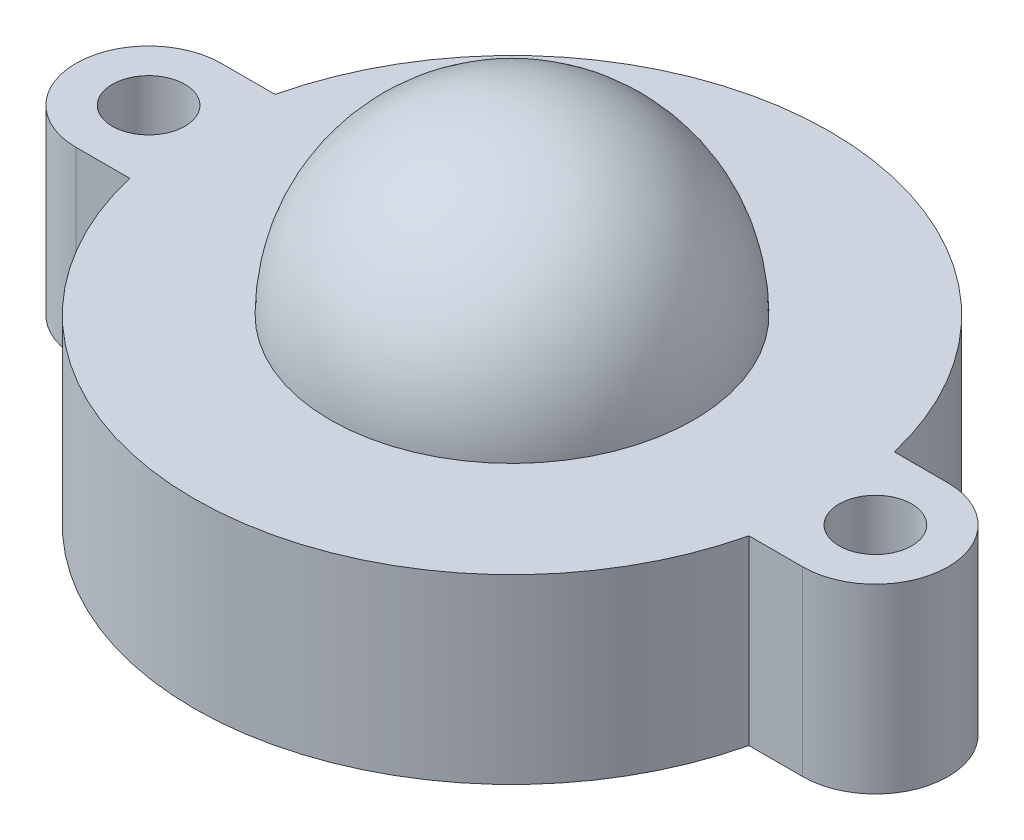
SolidWorks part; units mm, degrees
material "Chrome Stainless Steel"
ref_plane "Front Plane" through (0, 0, 0) normal (0, 0, 1) x (1, 0, 0)
ref_plane "Top Plane" through (0, 0, 0) normal (0, 1, 0) x (1, 0, 0)
ref_plane "Right Plane" through (0, 0, 0) normal (1, 0, 0) x (0, 0, -1)
sketch "Sketch1" plane through (0, 0, 0) normal (0, 1, 0) x (1, 0, 0)
  line L1 (-20, -4) -> (20, -4)
  line L2 (-20, -4) -> (-20, 4)
  line L3 (-20, 4) -> (20, 4)
  line L4 (20, -4) -> (20, 4)
  line L5 (-20, -4) -> (20, 4) construction
  line L6 (-20, 4) -> (20, -4) construction
  circle A0 centre (0, 0) radius 17.5
  arc A1 (-20, 4) -> (-20, -4) centre (-20, 0) ccw
  arc A2 (20, 4) -> (20, -4) centre (20, 0) cw
  circle A3 centre (-20, 0) radius 2
  circle A4 centre (20, 0) radius 2
  point P0 (0, 0)
  dimension "D2" = 35
  dimension "D4" = 4
  dimension "D5" = 4
  dimension "D1" = 40
  dimension "D3" = 8
extrude "Boss-Extrude1" add sketch "Sketch1" along normal blind 10 contours L1 A0 L3 | L1 A0 | L3 A0 | A3 L2 A1 | A3 L2 L1 A0 L3 | A4 L4 L3 A0 L1 | A4 L4 A2
sketch "Sketch2" plane through (0, 10, 0) normal (0, 1, 0) x (1, 0, 0)
  line L0 (0, 10) -> (0, -10)
  arc A0 (0, 10) -> (0, -10) centre (0, 0) ccw
  point P4 (0, 0)
  dimension "D1" = 20
revolve "Revolve1" add sketch "Sketch2" angle 180 about L0
